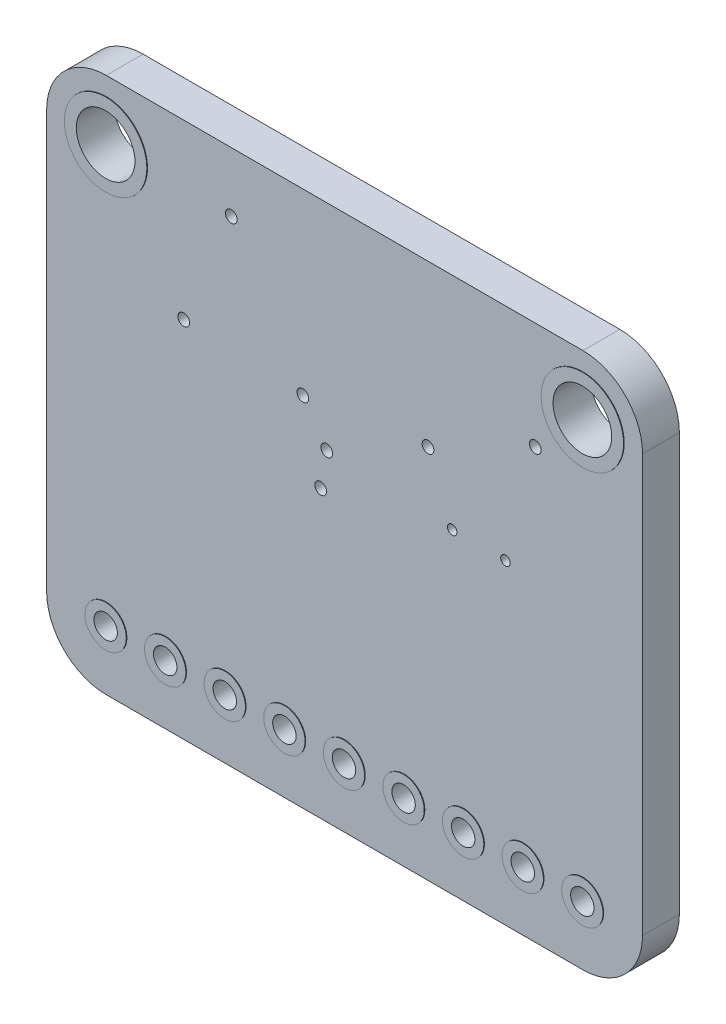
SolidWorks part; units mm, degrees
ref_plane "Front Plane" through (0, 0, 0) normal (0, 0, 1) x (1, 0, 0)
ref_plane "Top Plane" through (0, 0, 0) normal (0, 1, 0) x (1, 0, 0)
ref_plane "Right Plane" through (0, 0, 0) normal (1, 0, 0) x (0, 0, -1)
ref_plane "Plane1" through (0, 0, 0) normal (0, 0, -1) x (-1, 0, 0)
sketch "Sketch1" plane through (0, 0, 0) normal (0, 0, -1) x (-1, 0, 0)
  line L0 (-22.86, 0) -> (-2.54, 0)
  line L1 (0, 2.54) -> (0, 20.32)
  line L2 (-2.54, 22.86) -> (-22.86, 22.86)
  line L3 (-25.4, 20.32) -> (-25.4, 2.54)
  circle A0 centre (-22.86, 2.54) radius 0.5
  circle A1 centre (-17.78, 2.54) radius 0.5
  circle A2 centre (-12.7, 2.54) radius 0.5
  circle A3 centre (-7.62, 2.54) radius 0.5
  circle A4 centre (-2.54, 2.54) radius 0.5
  circle A5 centre (-7.874, 20.32) radius 0.25
  circle A6 centre (-10.922, 15.24) radius 0.25
  circle A7 centre (-11.684, 12.192) radius 0.25
  circle A8 centre (-17.285, 13.462) radius 0.203
  circle A9 centre (-20.828, 18.288) radius 0.25
  circle A10 centre (-5.842, 15.494) radius 0.25
  circle A11 centre (-16.256, 16.002) radius 0.25
  circle A12 centre (-19.558, 13.462) radius 0.203
  circle A13 centre (-11.938, 13.716) radius 0.25
  circle A14 centre (-2.54, 20.32) radius 1.25
  circle A15 centre (-22.86, 20.32) radius 1.25
  circle A16 centre (-5.08, 2.54) radius 0.5
  circle A17 centre (-10.16, 2.54) radius 0.5
  circle A18 centre (-15.24, 2.54) radius 0.5
  circle A19 centre (-20.32, 2.54) radius 0.5
  arc A20 (-25.4, 2.54) -> (-22.86, 0) centre (-22.86, 2.54) ccw
  arc A21 (-2.54, 0) -> (0, 2.54) centre (-2.54, 2.54) ccw
  arc A22 (0, 20.32) -> (-2.54, 22.86) centre (-2.54, 20.32) ccw
  arc A23 (-22.86, 22.86) -> (-25.4, 20.32) centre (-22.86, 20.32) ccw
extrude "Boss-Extrude1" add sketch "Sketch1" against normal blind 1.57
sketch "Sketch2" plane through (0, 0, 1.57) normal (0, 0, 1) x (1, 0, 0)
  circle A0 centre (22.86, 20.32) radius 1.25 construction
  circle A1 centre (2.54, 20.32) radius 1.25 construction
  circle A2 centre (22.86, 20.32) radius 1.25
  circle A3 centre (2.54, 20.32) radius 1.25
  circle A4 centre (2.54, 20.32) radius 1.758
  circle A5 centre (22.86, 20.32) radius 1.758
  dimension "D1" = 0.508
extrude "Boss-Extrude2" add sketch "Sketch2" along normal blind 0.0254
ref_plane "Plane2" through (0, 0, 0.785) normal (0, 0, 1) x (1, 0, 0)
mirror "Mirror1" about plane through (0, 0, 0.785) normal (0, 0, 1) of "Boss-Extrude2"
sketch "Sketch3" plane through (0, 0, 1.57) normal (0, 0, 1) x (1, 0, 0)
  circle A0 centre (22.86, 2.54) radius 0.5 construction
  circle A1 centre (20.32, 2.54) radius 0.5 construction
  circle A2 centre (17.78, 2.54) radius 0.5 construction
  circle A3 centre (15.24, 2.54) radius 0.5 construction
  circle A4 centre (12.7, 2.54) radius 0.5 construction
  circle A5 centre (10.16, 2.54) radius 0.5 construction
  circle A6 centre (7.62, 2.54) radius 0.5 construction
  circle A7 centre (5.08, 2.54) radius 0.5 construction
  circle A8 centre (2.54, 2.54) radius 0.5 construction
  circle A9 centre (22.86, 2.54) radius 0.5
  circle A10 centre (20.32, 2.54) radius 0.5
  circle A11 centre (17.78, 2.54) radius 0.5
  circle A12 centre (15.24, 2.54) radius 0.5
  circle A13 centre (12.7, 2.54) radius 0.5
  circle A14 centre (10.16, 2.54) radius 0.5
  circle A15 centre (7.62, 2.54) radius 0.5
  circle A16 centre (5.08, 2.54) radius 0.5
  circle A17 centre (2.54, 2.54) radius 0.5
  circle A18 centre (2.54, 2.54) radius 0.881
  circle A19 centre (5.08, 2.54) radius 0.881
  circle A20 centre (7.62, 2.54) radius 0.881
  circle A21 centre (10.16, 2.54) radius 0.881
  circle A22 centre (12.7, 2.54) radius 0.881
  circle A23 centre (15.24, 2.54) radius 0.881
  circle A24 centre (17.78, 2.54) radius 0.881
  circle A25 centre (20.32, 2.54) radius 0.881
  circle A26 centre (22.86, 2.54) radius 0.881
  dimension "D1" = 0.381
extrude "Boss-Extrude3" add sketch "Sketch3" along normal blind 0.0254
mirror "Mirror2" about plane through (0, 0, 0.785) normal (0, 0, 1) of "Boss-Extrude3"
